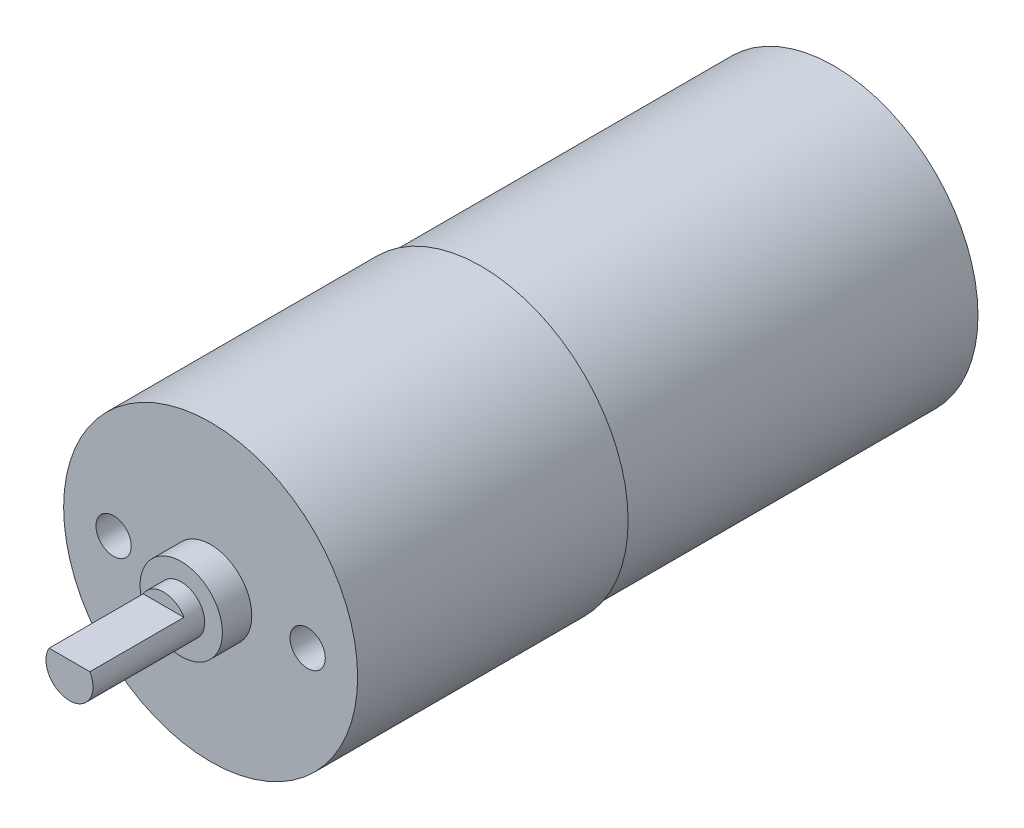
SolidWorks part; units mm, degrees
ref_plane "Front Plane" through (0, 0, 0) normal (0, 0, 1) x (1, 0, 0)
ref_plane "Top Plane" through (0, 0, 0) normal (0, 1, 0) x (1, 0, 0)
ref_plane "Right Plane" through (0, 0, 0) normal (1, 0, 0) x (0, 0, -1)
sketch "Sketch1" plane through (0, 0, 0) normal (0, 0, 1) x (1, 0, 0)
  circle A0 centre (0, 0) radius 12.25
  dimension "D1" = 24.5
extrude "Boss-Extrude1" add sketch "Sketch1" along normal blind 30
sketch "Sketch2" plane through (0, 0, 30) normal (0, 0, 1) x (1, 0, 0)
  circle A0 centre (0, 0) radius 12.5
  dimension "D1" = 25
extrude "Boss-Extrude2" add sketch "Sketch2" along normal blind 23
sketch "Sketch7" plane through (0, 0, 53) normal (0, 0, 1) x (1, 0, 0)
  line L0 (12.5, 0) -> (-12.5, 0)
  line L1 (12.5, 0) -> (8.25, 0)
  line L2 (-12.5, 0) -> (-8.25, 0)
  circle A0 centre (0, 0) radius 12.5 construction
  circle A1 centre (-8.25, 0) radius 1.5
  circle A2 centre (8.25, 0) radius 1.5
  dimension "D3" = 3
  dimension "D4" = 3
  dimension "D1" = 4.25
  dimension "D2" = 4.25
extrude "Cut-Extrude1" cut sketch "Sketch7" against normal blind 5 contours L0 A1 | L0 A1 | L1 A2 L0 | L0 A2 L1
sketch "Sketch3" plane through (0, 0, 53) normal (0, 0, 1) x (1, 0, 0)
  circle A0 centre (0, 0) radius 3.5
  dimension "D1" = 7
extrude "Boss-Extrude3" add sketch "Sketch3" along normal blind 2.5
sketch "Sketch4" plane through (0, 0, 55.5) normal (0, 0, 1) x (1, 0, 0)
  circle A0 centre (0, 0) radius 2
  dimension "D1" = 4
extrude "Boss-Extrude4" add sketch "Sketch4" along normal blind 1.5
sketch "Sketch5" plane through (0, 0, 57) normal (0, 0, 1) x (1, 0, 0)
  line L0 (-1.7321, 1) -> (1.7321, 1)
  circle A0 centre (0, 0) radius 2
  circle M1 centre (0, 0) radius 2
  dimension "D2" = 4
  dimension "D1" = 1
extrude "Boss-Extrude5" add sketch "Sketch5" along normal blind 8 contours L0 M1
sketch "Sketch6" plane through (0, 0, 0) normal (0, 0, -1) x (-1, 0, 0)
  circle A0 centre (0, 0) radius 3.75
  dimension "D1" = 7.5
extrude "Boss-Extrude6" add sketch "Sketch6" along normal blind 2
fillet "Fillet1" radius 1 1 edges at (-3.75, 0, -2)
